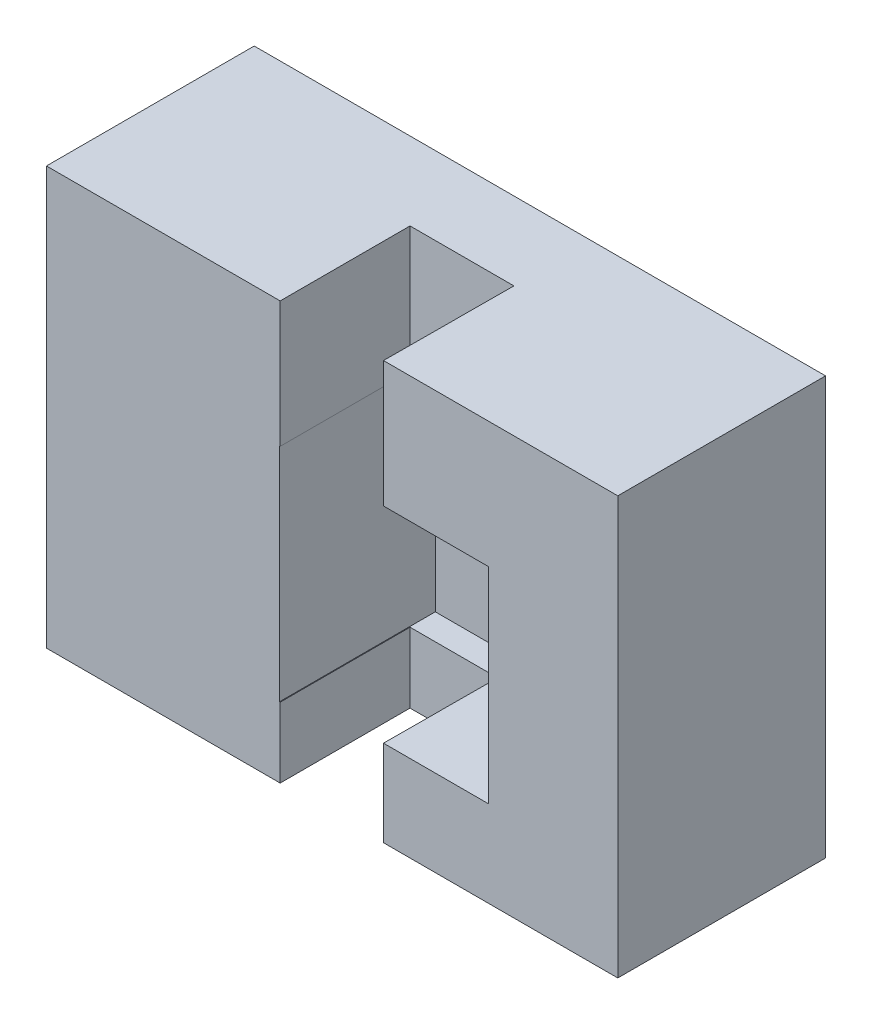
SolidWorks part; units mm, degrees
ref_plane "Ön Düzlem" through (0, 0, 0) normal (0, 0, 1) x (1, 0, 0)
ref_plane "Üst Düzlem" through (0, 0, 0) normal (0, 1, 0) x (1, 0, 0)
ref_plane "Sağ Düzlem" through (0, 0, 0) normal (1, 0, 0) x (0, 0, -1)
sketch "Çizim1" plane through (0, 0, 0) normal (0, 0, 1) x (1, 0, 0)
  line L1 (-55, 40.2) -> (55, 40.2)
  line L2 (-55, 40.2) -> (-55, -40.2)
  line L3 (-55, -40.2) -> (55, -40.2)
  line L4 (55, 40.2) -> (55, -40.2)
  point P4 (0, 40.2)
  point P6 (-55, 0)
  dimension "D1" = 110
  dimension "D2" = 80.4
extrude "Yükseklik-Ekstrüzyon1" add sketch "Çizim1" along normal blind 40
sketch "Çizim2" plane through (0, 0, 40) normal (0, 0, 1) x (1, 0, 0)
  line L0 (30.0976, 15.9478) -> (-10.1339, 15.9478)
  line L1 (-10.1339, 15.9478) -> (-10.1339, -26.7105)
  line L2 (-10.1339, -26.7105) -> (9.889, -26.7105)
  line L3 (9.889, -26.7105) -> (9.889, -23.5994)
  line L4 (9.889, -23.5994) -> (30.0976, -23.5994)
  line L5 (30.0976, -23.5994) -> (30.0976, 15.9478)
extrude "Kes-Ekstrüzyon1" cut sketch "Çizim2" against normal blind 30
sketch "Çizim3" plane through (0, 40.2, 0) normal (0, 1, 0) x (1, 0, 0)
  line L0 (9.889, -40) -> (10, -15)
  line L1 (10, -15) -> (-10, -15)
  line L2 (-10, -15) -> (-10, -40)
  line L3 (55, -40) -> (-55, -40) construction
  line L4 (-10, -395) -> (-10, -15) construction
  line L5 (-10, -40) -> (9.889, -40)
extrude "Kes-Ekstrüzyon2" cut sketch "Çizim3" against normal through all
